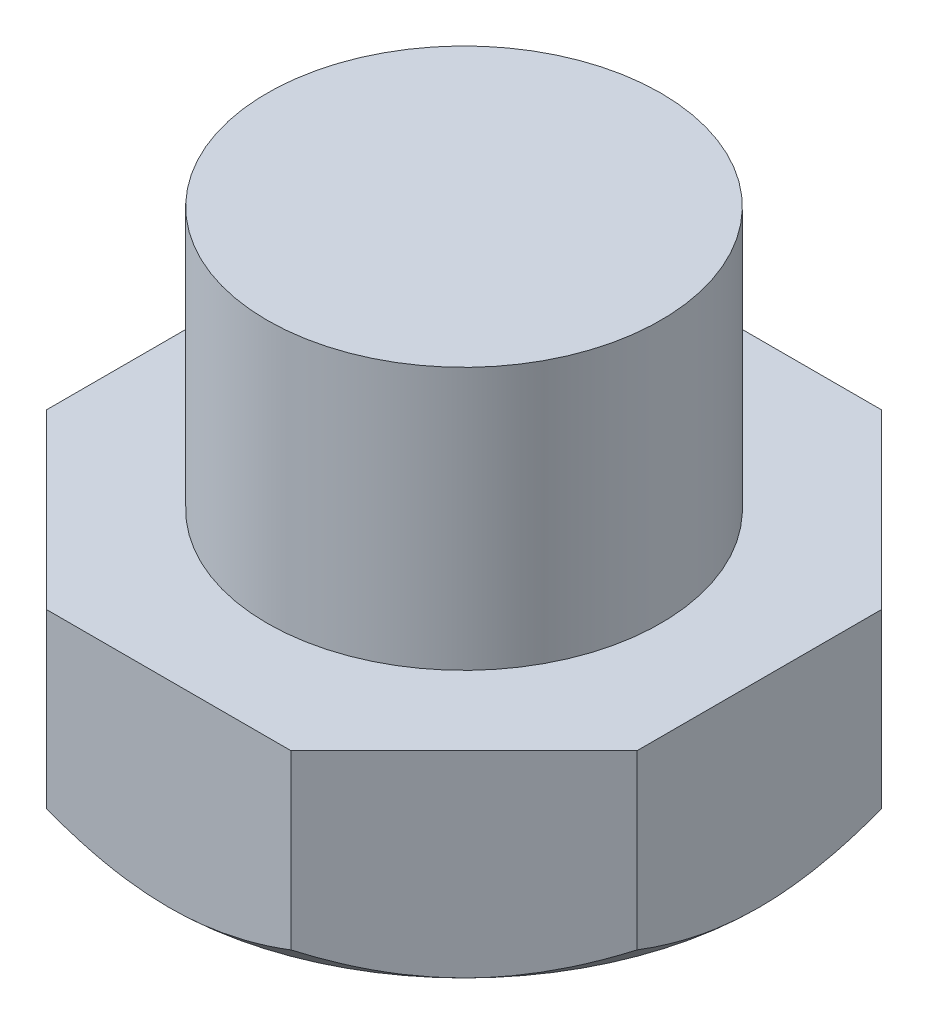
SolidWorks part; units mm, degrees
ref_plane "Front Plane" through (0, 0, 0) normal (0, 0, 1) x (1, 0, 0)
ref_plane "Top Plane" through (0, 0, 0) normal (0, 1, 0) x (1, 0, 0)
ref_plane "Right Plane" through (0, 0, 0) normal (1, 0, 0) x (0, 0, -1)
sketch "Sketch1" plane through (0, 0, 0) normal (0, 1, 0) x (1, 0, 0)
  circle A0 centre (0, 0) radius 15
  dimension "D1" = 30
extrude "Boss-Extrude1" add sketch "Sketch1" along normal blind 20
sketch "Sketch2" plane through (0, 0, 0) normal (0, -1, 0) x (1, 0, 0)
  line L7 (22.5, -9.3198) -> (22.5, 9.3198)
  line L8 (22.5, 9.3198) -> (9.3198, 22.5)
  line L9 (9.3198, 22.5) -> (-9.3198, 22.5)
  line L10 (-9.3198, 22.5) -> (-22.5, 9.3198)
  line L11 (-22.5, 9.3198) -> (-22.5, -9.3198)
  line L12 (-22.5, -9.3198) -> (-9.3198, -22.5)
  line L13 (-9.3198, -22.5) -> (9.3198, -22.5)
  line L14 (9.3198, -22.5) -> (22.5, -9.3198)
  circle A0 centre (0, 0) radius 22.5 construction
  dimension "D1" = 45
extrude "Boss-Extrude2" add sketch "Sketch2" along normal blind 15
sketch "Sketch3" plane through (0, -15, 0) normal (0, -1, 0) x (-1, 0, 0)
  circle A0 centre (0, 0) radius 22.5
extrude "Cut-Extrude1" cut sketch "Sketch3" against normal blind 20 draft 45 flip side to cut
